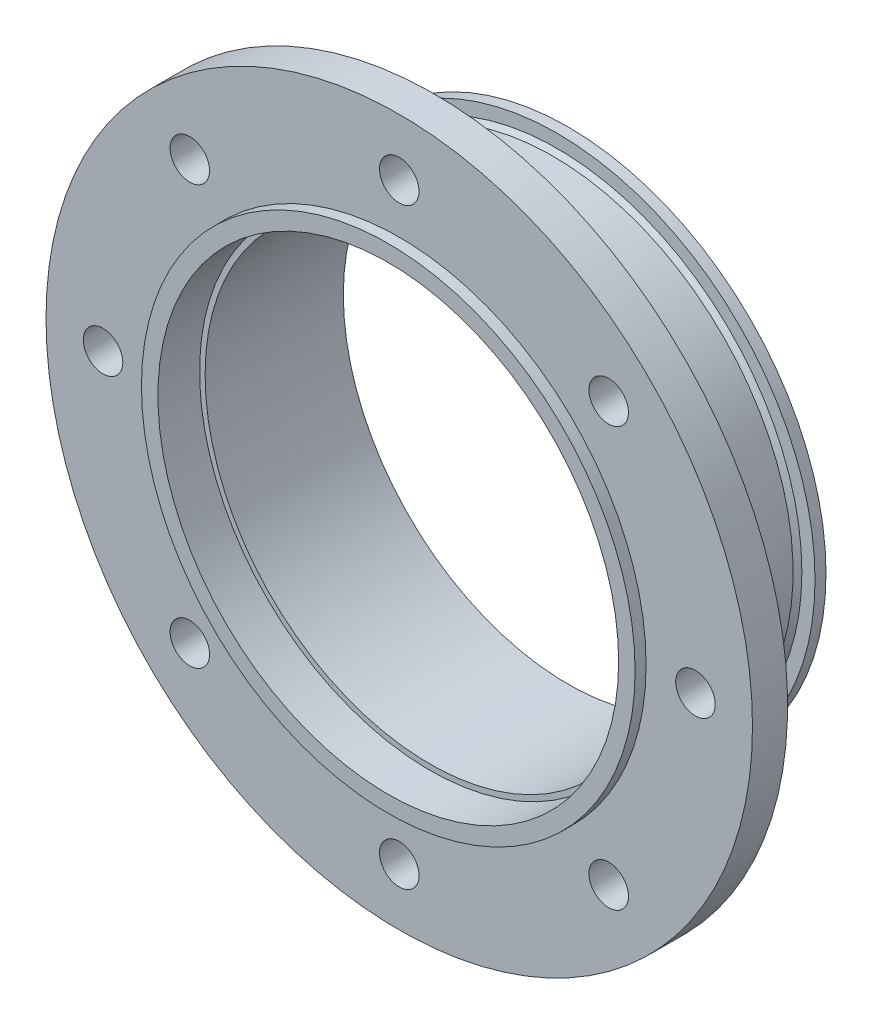
SolidWorks part; units mm, degrees
ref_plane "Front Plane" through (0, 0, 0) normal (0, 0, 1) x (1, 0, 0)
ref_plane "Top Plane" through (0, 0, 0) normal (0, 1, 0) x (1, 0, 0)
ref_plane "Right Plane" through (0, 0, 0) normal (1, 0, 0) x (0, 0, -1)
sketch "Sketch1" plane through (0, 0, 0) normal (0, 0, 1) x (1, 0, 0)
  circle A0 centre (0, 0) radius 161
  circle A2 centre (0, 0) radius 102.5
  dimension "D1" = 322
  dimension "D2" = 205
extrude "Boss-Extrude1" add sketch "Sketch1" along normal blind 82 contours A0 | A2
sketch "Sketch2" plane through (0, 0, 82) normal (0, 0, 1) x (1, 0, 0)
  circle A0 centre (0, 0) radius 135
  circle A1 centre (0, 135) radius 9
  dimension "D1" = 270
  dimension "D2" = 18
extrude "Cut-Extrude1" cut sketch "Sketch2" against normal through all contours A1
pattern_circular "CirPattern1" count 8 over 360 about axis through (0, 0, 0) along (0, 0, 1) of "Cut-Extrude1"
sketch "Sketch3" plane through (0, 0, 0) normal (0, 0, -1) x (-1, 0, 0)
  circle A0 centre (0, 0) radius 161
  circle A1 centre (0, 0) radius 109.5
  dimension "D1" = 219
extrude "Cut-Extrude2" cut sketch "Sketch3" against normal blind 61
sketch "Sketch4" plane through (0, 0, 0) normal (0, 0, -1) x (-1, 0, 0)
  circle A0 centre (0, 0) radius 117.5
  circle A1 centre (0, 0) radius 109.5
  dimension "D1" = 235
extrude "Boss-Extrude3" add sketch "Sketch4" against normal blind 5
sketch "Sketch6" plane through (0, 0, 82) normal (0, 0, 1) x (1, 0, 0)
  circle A0 centre (0, 0) radius 112.5
  circle A1 centre (0, 0) radius 161
  dimension "D1" = 225
extrude "Cut-Extrude3" cut sketch "Sketch6" against normal blind 5
chamfer "Chamfer1" distance 2 angle 45 1 edges at (-109.5, 0, 5)
chamfer "Chamfer2" distance 2 angle 45 1 edges at (-109.5, 0, 61)
sketch "Sketch8" plane through (0, 0, 82) normal (0, 0, 1) x (1, 0, 0)
  circle A0 centre (0, 0) radius 105
  dimension "D1" = 210
extrude "Cut-Extrude5" cut sketch "Sketch8" against normal blind 19
